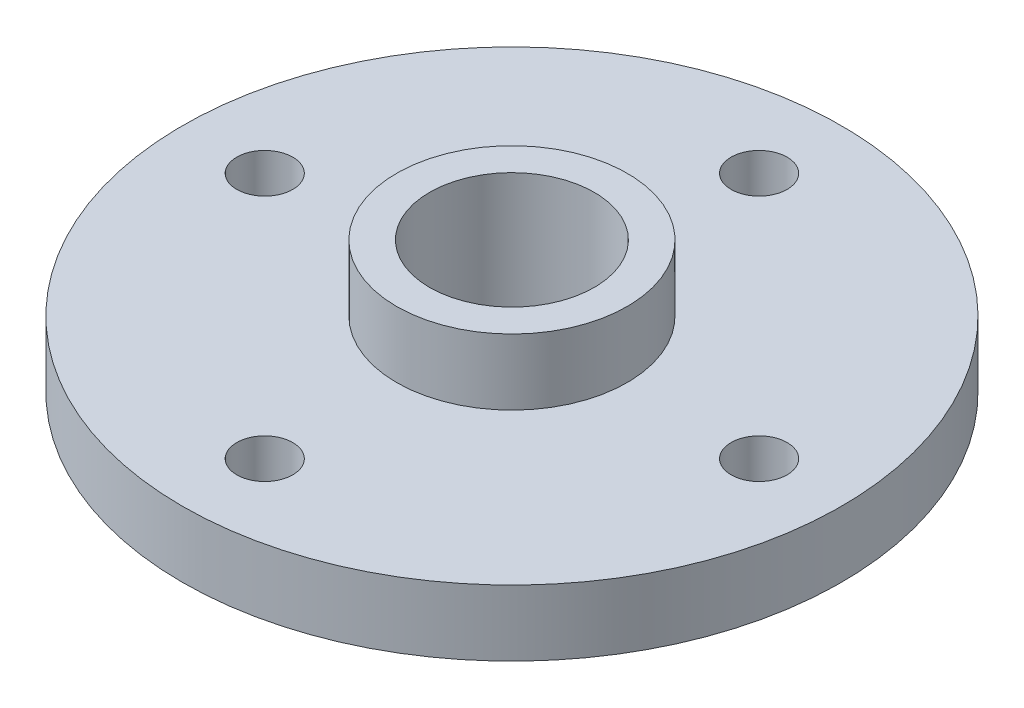
SolidWorks part; units mm, degrees
ref_plane "Front Plane" through (0, 0, 0) normal (0, 0, 1) x (1, 0, 0)
ref_plane "Top Plane" through (0, 0, 0) normal (0, 1, 0) x (1, 0, 0)
ref_plane "Right Plane" through (0, 0, 0) normal (1, 0, 0) x (0, 0, -1)
sketch "Sketch1" plane through (0, 0, 0) normal (0, 1, 0) x (1, 0, 0)
  circle A0 centre (0, 0) radius 10
  dimension "D1" = 20
extrude "Boss-Extrude1" add sketch "Sketch1" along normal blind 2
sketch "Sketch2" plane through (0, 2, 0) normal (0, 1, 0) x (1, 0, 0)
  circle A0 centre (0, 0) radius 3.5
  dimension "D1" = 7
extrude "Boss-Extrude2" add sketch "Sketch2" along normal blind 2
sketch "Sketch3" plane through (0, 4, 0) normal (0, 1, 0) x (1, 0, 0)
  circle A0 centre (0, 0) radius 2.5
  dimension "D1" = 5
extrude "Cut-Extrude1" cut sketch "Sketch3" against normal through all
sketch "Sketch4" plane through (0, 2, 0) normal (0, 1, 0) x (1, 0, 0)
  circle A0 centre (0, 0) radius 7.5
  circle A1 centre (0, 7.5) radius 0.85
  circle A2 centre (-7.5, 0) radius 0.85
  circle A3 centre (7.5, 0) radius 0.85
  circle A4 centre (0, -7.5) radius 0.85
  dimension "D1" = 15
  dimension "D2" = 1.7
  dimension "D3" = 1.7
  dimension "D4" = 1.7
  dimension "D5" = 1.7
extrude "Cut-Extrude2" cut sketch "Sketch4" against normal through all contours A0 A1 | A0 A1 | A0 A3 | A0 A3 | A0 A2 | A0 A2 | A0 A4 | A0 A4
